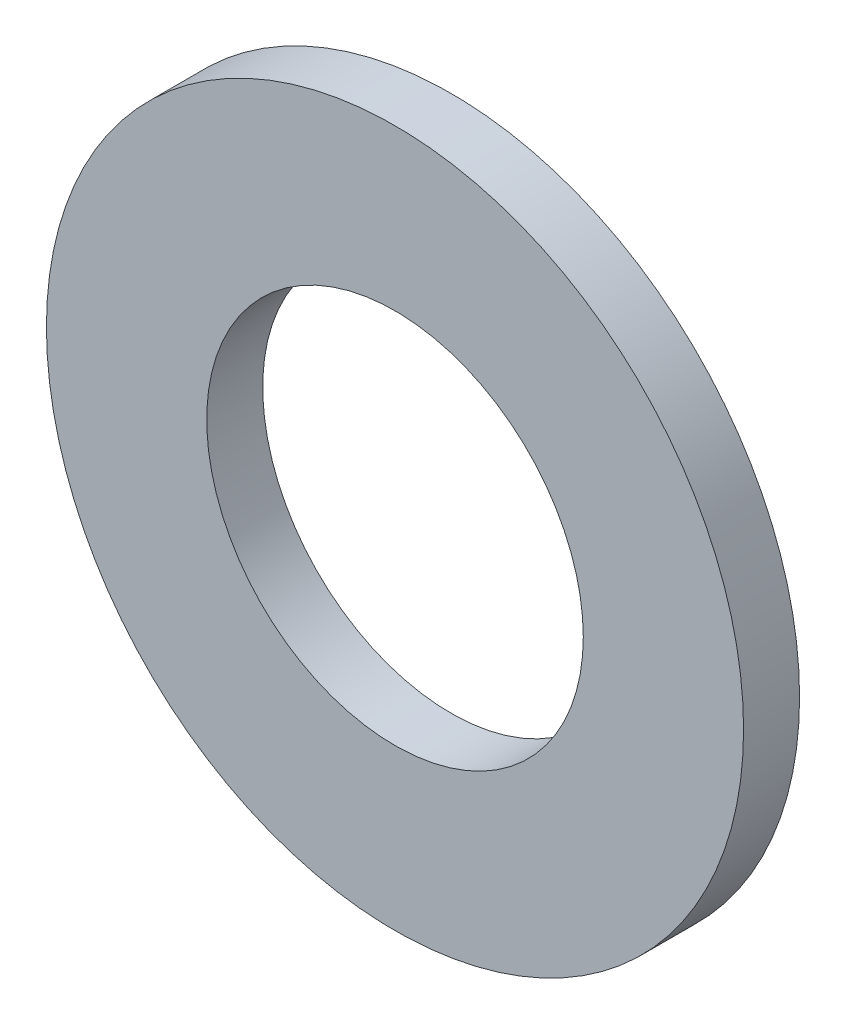
SolidWorks part; units mm, degrees
ref_plane "Front" through (0, 0, 0) normal (0, 0, 1) x (1, 0, 0)
ref_plane "Top" through (0, 0, 0) normal (0, 1, 0) x (1, 0, 0)
ref_plane "Right" through (0, 0, 0) normal (1, 0, 0) x (0, 0, -1)
sketch "Sketch1" plane through (0, 0, 0) normal (0, 0, 1) x (1, 0, 0)
  circle A0 centre (0, 0) radius 6.3246
  circle A1 centre (0, 0) radius 3.4163
extrude "Extrude1" add sketch "Sketch1" along normal blind 1.016
